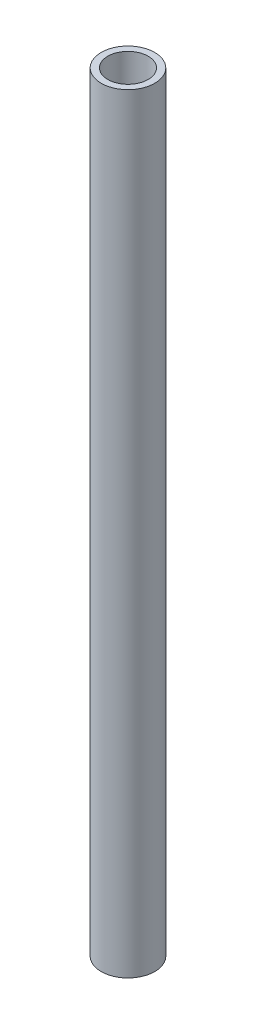
SolidWorks part; units mm, degrees
material "Thornel Mat VMA"
ref_plane "Front Plane" through (0, 0, 0) normal (0, 0, 1) x (1, 0, 0)
ref_plane "Top Plane" through (0, 0, 0) normal (0, 1, 0) x (1, 0, 0)
ref_plane "Right Plane" through (0, 0, 0) normal (1, 0, 0) x (0, 0, -1)
sketch "Sketch1" plane through (0, 0, 0) normal (0, 1, 0) x (1, 0, 0)
  circle A1 centre (0, 0) radius 3.175
  circle A2 centre (0, 0) radius 4.2037
  dimension "D1" = 6.35
  dimension "D2" = 8.4074
extrude "Boss-Extrude1" add sketch "Sketch1" along normal blind 120.904
